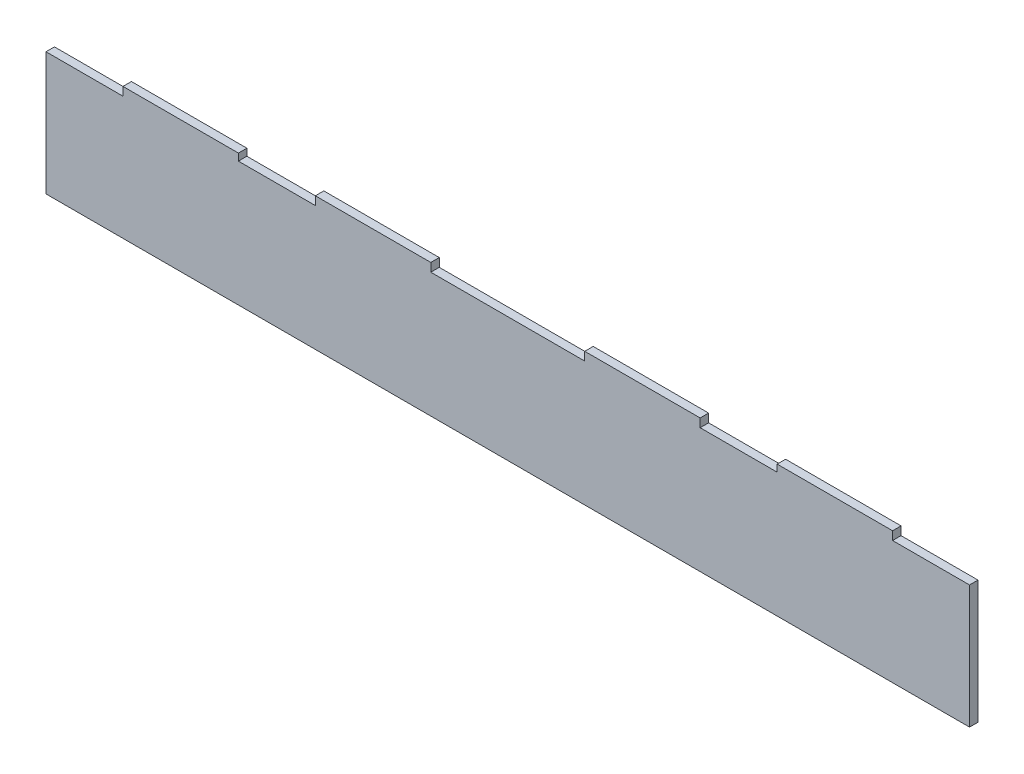
SolidWorks part; units mm, degrees
ref_plane "Front Plane" through (0, 0, 0) normal (0, 0, 1) x (1, 0, 0)
ref_plane "Top Plane" through (0, 0, 0) normal (0, 1, 0) x (1, 0, 0)
ref_plane "Right Plane" through (0, 0, 0) normal (1, 0, 0) x (0, 0, -1)
sketch "Sketch1" plane through (0, 0, 0) normal (0, 0, 1) x (1, 0, 0)
  line L0 (136.134, -17.0167) -> (136.134, 71.8833) construction
  line L1 (-117.866, 69.8513) -> (-41.666, 69.8513)
  line L2 (-168.666, -17.0167) -> (-168.666, 64.2633)
  line L3 (-168.666, -17.0167) -> (440.934, -17.0167)
  line L4 (186.934, 70.8281) -> (186.934, 65.2401)
  line L5 (9.134, 70.8281) -> (85.334, 70.8281)
  line L6 (263.134, 70.8281) -> (186.934, 70.8281)
  line L7 (263.134, 70.8281) -> (263.134, 65.2401)
  line L8 (-168.666, 64.2633) -> (-117.866, 64.2633)
  line L9 (-117.866, 69.8513) -> (-117.866, 64.2633)
  line L10 (313.934, 65.2401) -> (263.134, 65.2401)
  line L11 (-41.666, 69.8513) -> (-41.666, 65.2401)
  line L12 (-41.666, 65.2401) -> (9.134, 65.2401)
  line L13 (9.134, 70.8281) -> (9.134, 65.2401)
  line L14 (313.934, 69.8513) -> (313.934, 65.2401)
  line L15 (85.334, 70.8281) -> (85.334, 65.2401)
  line L16 (85.334, 65.2401) -> (186.934, 65.2401)
  line L17 (390.134, 69.8513) -> (313.934, 69.8513)
  line L18 (390.134, 69.8513) -> (390.134, 64.2633)
  line L19 (440.934, 64.2633) -> (390.134, 64.2633)
  line L20 (440.934, -17.0167) -> (440.934, 64.2633)
  point P3 (136.134, 65.2401)
  dimension "D1" = 609.6
  dimension "D3" = 50.8
  dimension "D5" = 76.2
  dimension "D6" = 76.2
  dimension "D4" = 5.588
  dimension "D2" = 81.28
extrude "Boss-Extrude1" add sketch "Sketch1" along normal blind 5.588
equation "\"width\"= 9in"
equation "\"Height\"= 18in"
equation "\"thick\"= 0.22"
equation "\"D1@Boss-Extrude1\"=\"thick\""
equation "\"D4@Sketch1\"=\"thick\""
